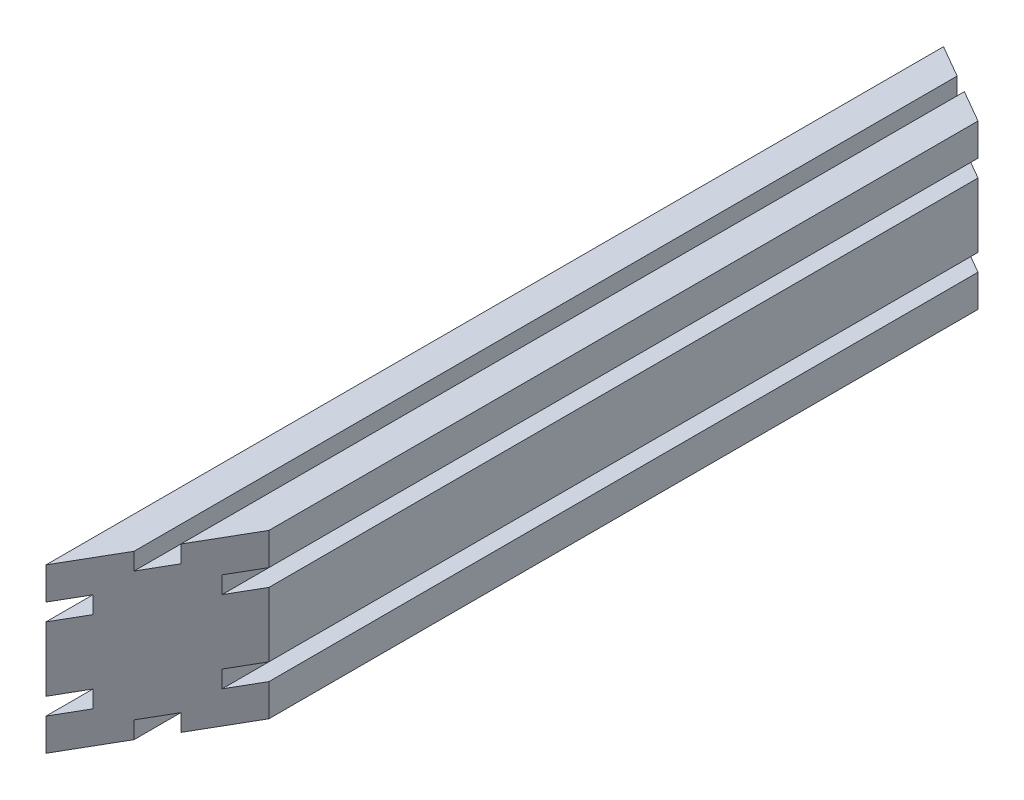
SolidWorks part; units mm, degrees
ref_plane "Front Plane" through (0, 0, 0) normal (0, 0, 1) x (1, 0, 0)
ref_plane "Top Plane" through (0, 0, 0) normal (0, 1, 0) x (1, 0, 0)
ref_plane "Right Plane" through (0, 0, 0) normal (1, 0, 0) x (0, 0, -1)
sketch "Sketch1" plane through (0, 0, 0) normal (0, 0, 1) x (1, 0, 0)
  line L0 (-19.05, -38.1) -> (-4, -38.1)
  line L1 (-4, -38.1) -> (-4, -30.1)
  line L2 (-4, -30.1) -> (4, -30.1)
  line L3 (4, -30.1) -> (4, -38.1)
  line L4 (4, -38.1) -> (19.05, -38.1)
  line L5 (19.05, -38.1) -> (19.05, -23.05)
  line L6 (19.05, -23.05) -> (11.05, -23.05)
  line L7 (11.05, -23.05) -> (11.05, -15.05)
  line L8 (11.05, -15.05) -> (19.05, -15.05)
  line L9 (19.05, -15.05) -> (19.05, 15.05)
  line L10 (19.05, 15.05) -> (11.05, 15.05)
  line L11 (11.05, 15.05) -> (11.05, 23.05)
  line L12 (11.05, 23.05) -> (19.05, 23.05)
  line L13 (19.05, 23.05) -> (19.05, 38.1)
  line L14 (19.05, 38.1) -> (4, 38.1)
  line L15 (4, 38.1) -> (4, 30.1)
  line L16 (4, 30.1) -> (-4, 30.1)
  line L17 (-4, 30.1) -> (-4, 38.1)
  line L18 (-4, 38.1) -> (-19.05, 38.1)
  line L19 (-19.05, 38.1) -> (-19.05, 23.05)
  line L20 (-19.05, 23.05) -> (-11.05, 23.05)
  line L21 (-11.05, 23.05) -> (-11.05, 15.05)
  line L22 (-11.05, 15.05) -> (-19.05, 15.05)
  line L23 (-19.05, 15.05) -> (-19.05, -15.05)
  line L24 (-19.05, -15.05) -> (-11.05, -15.05)
  line L25 (-11.05, -15.05) -> (-11.05, -23.05)
  line L26 (-11.05, -23.05) -> (-19.05, -23.05)
  line L27 (-19.05, -23.05) -> (-19.05, -38.1)
extrude "Profile" add sketch "Sketch1" along normal blind 419.1
sketch "Sketch2" plane through (0, 0, 0) normal (0, 1, 0) x (1, 0, 0)
  line L0 (-19.05, -419.1) -> (25, -342.8)
  line L1 (25, -342.8) -> (25, -430)
  line L2 (25, -430) -> (-19.05, -419.1)
extrude "Miter1" cut sketch "Sketch2" against normal through all and the other way through all
sketch "Sketch3" plane through (0, 0, 0) normal (0, 1, 0) x (1, 0, 0)
  line L0 (-19.05, 0) -> (25, 10)
  line L1 (25, 10) -> (25, -25.43)
  line L2 (25, -25.43) -> (-19.05, 0)
extrude "Miter2" cut sketch "Sketch3" against normal through all and the other way through all
equation "\"length\" = 419.1mm"
equation "\"D1@Profile\" = \"length\""
